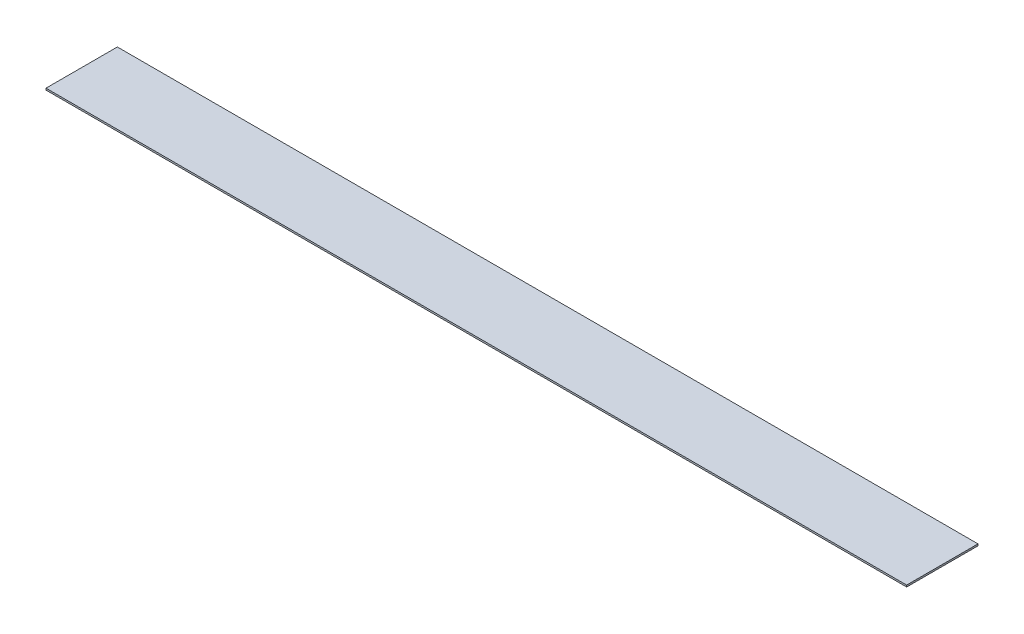
SolidWorks part; units mm, degrees
material "BUTYL"
ref_plane "Ön Düzlem" through (0, 0, 0) normal (0, 0, 1) x (1, 0, 0)
ref_plane "Üst Düzlem" through (0, 0, 0) normal (0, 1, 0) x (1, 0, 0)
ref_plane "Sağ Düzlem" through (0, 0, 0) normal (1, 0, 0) x (0, 0, -1)
sketch "Sketch1" plane through (0, 0, 0) normal (0, 1, 0) x (1, 0, 0)
  line L1 (-249.86, 20.71) -> (249.86, 20.71)
  line L2 (-249.86, 20.71) -> (-249.86, -20.71)
  line L3 (-249.86, -20.71) -> (249.86, -20.71)
  line L4 (249.86, 20.71) -> (249.86, -20.71)
  line L5 (-249.86, 20.71) -> (249.86, -20.71) construction
  line L6 (-249.86, -20.71) -> (249.86, 20.71) construction
  point P0 (0, 0)
  dimension "D1" = 41.42
  dimension "D2" = 499.72
extrude "Boss-Extrude1" add sketch "Sketch1" along normal blind 1
